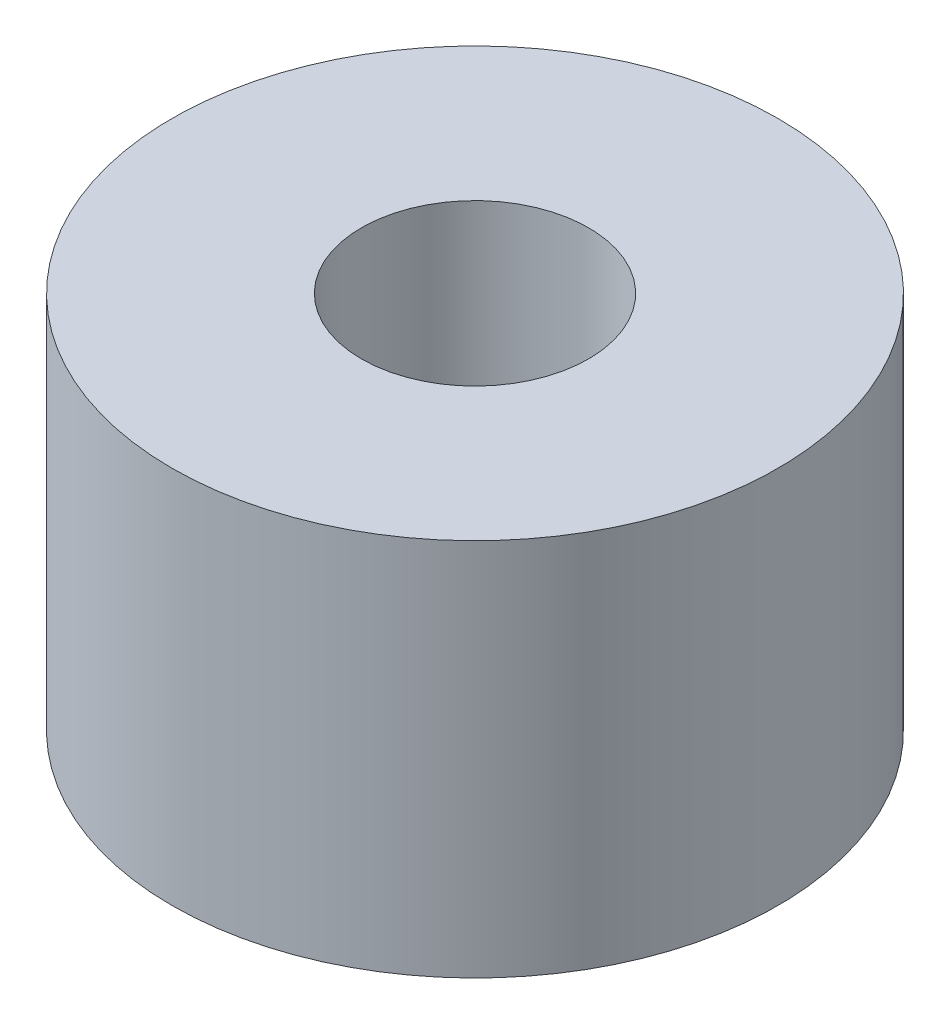
SolidWorks part; units mm, degrees
ref_plane "前视基准面" through (0, 0, 0) normal (0, 0, 1) x (1, 0, 0)
ref_plane "上视基准面" through (0, 0, 0) normal (0, 1, 0) x (1, 0, 0)
ref_plane "右视基准面" through (0, 0, 0) normal (1, 0, 0) x (0, 0, -1)
sketch "草图1" plane through (0, 0, 0) normal (0, 1, 0) x (1, 0, 0)
  circle A0 centre (0, 0) radius 4
  circle A1 centre (0, 0) radius 1.5
extrude "凸台-拉伸1" add sketch "草图1" along normal blind 5
